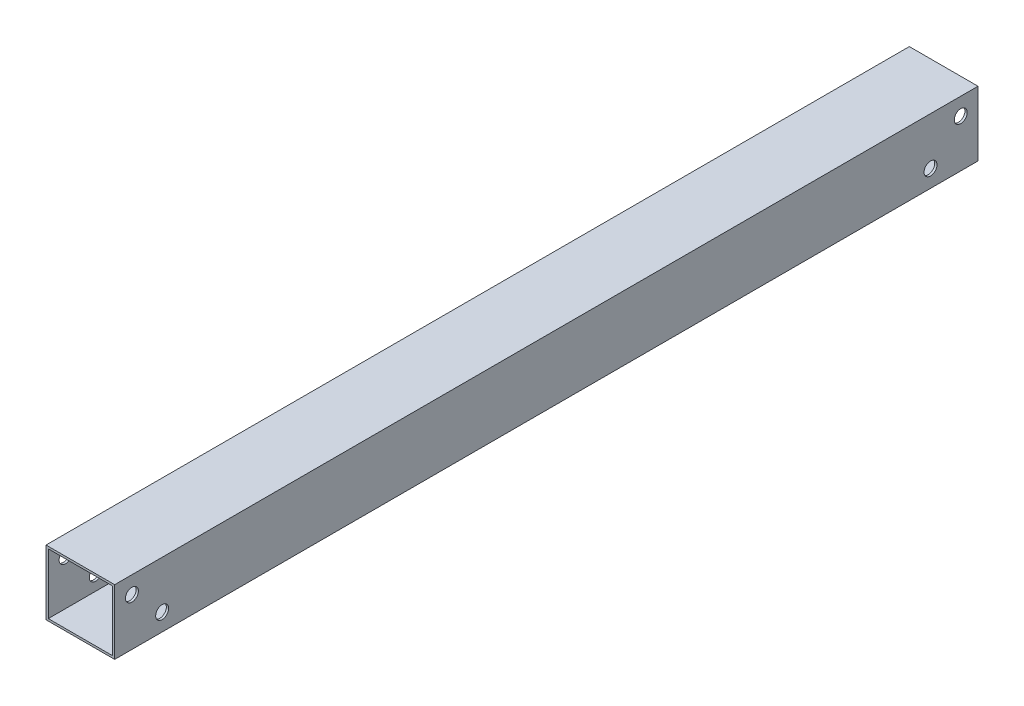
SolidWorks part; units mm, degrees
material "Alliage 1060"
ref_plane "Plan de face" through (0, 0, 0) normal (0, 0, 1) x (1, 0, 0)
ref_plane "Plan de dessus" through (0, 0, 0) normal (0, 1, 0) x (1, 0, 0)
ref_plane "Plan de droite" through (0, 0, 0) normal (1, 0, 0) x (0, 0, -1)
sketch "Esquisse1" plane through (0, 0, 0) normal (0, 0, 1) x (1, 0, 0)
  line L0 (0, 0) -> (15.9091, 15) construction
  line L1 (0, 0) -> (15.9091, 0)
  line L2 (0, 0) -> (0, 15)
  line L3 (0, 15) -> (15.9091, 15)
  line L4 (15.9091, 0) -> (15.9091, 15)
  line L5 (0, 15) -> (15.9091, 0) construction
  line L7 (0.5303, 14.5) -> (15.3788, 14.5)
  line L8 (0.5303, 14.5) -> (0.5303, 0.5)
  line L9 (0.5303, 0.5) -> (15.3788, 0.5)
  line L10 (15.3788, 14.5) -> (15.3788, 0.5)
  line L11 (0.5303, 14.5) -> (15.3788, 0.5) construction
  line L12 (0.5303, 0.5) -> (15.3788, 14.5) construction
  point P5 (7.9546, 7.5)
  dimension "D1" = 14
  dimension "D2" = 15
extrude "Boss.-Extru.1" add sketch "Esquisse1" against normal blind 200
sketch "Esquisse2" plane through (0, 15, 0) normal (0, 1, 0) x (1, 0, 0)
  line L0 (7.9546, 0) -> (7.9546, 200) construction
  line L1 (15.9091, 0) -> (0, 0) construction
  line L2 (15.9091, 200) -> (0, 200) construction
  line L3 (0, 200) -> (7.9546, 200) construction
  line L4 (7.9546, 200) -> (15.9091, 200) construction
  line L5 (15.9091, 200) -> (11.9318, 200) construction
  line L6 (11.9318, 200) -> (11.9318, 0) construction
  line L7 (11.9318, 0) -> (11.9318, 200) construction
  line L8 (11.9318, 200) -> (3.9773, 200) construction
  line L9 (3.9773, 200) -> (3.9773, 0) construction
  line L10 (3.9773, 200) -> (7.9546, 200) construction
  line L11 (7.9546, 200) -> (11.9318, 200) construction
  line L12 (9.9432, 200) -> (9.9432, 0) construction
  line L13 (9.9432, 0) -> (7.9546, 0) construction
  line L14 (7.9546, 0) -> (3.9773, 0) construction
  line L15 (3.9773, 0) -> (5.9659, 0) construction
  line L16 (5.9659, 0) -> (5.9659, 200) construction
  circle A2 centre (5.9659, 122.5818) radius 4
  circle A3 centre (9.9432, 67.5818) radius 4
  dimension "D1" = 8
  dimension "D2" = 8
  dimension "D3" = 55
sketch "Esquisse6" plane through (15.9091, 0, 0) normal (1, 0, 0) x (0, 0, -1)
  line L0 (0, 15) -> (0, 7.5) construction
  line L1 (0, 0) -> (0, 15) construction
  line L2 (0, 7.5) -> (0, 0) construction
  line L3 (0, 0) -> (0, 3.75) construction
  line L5 (200, 0) -> (200, 15) construction
  line L6 (200, 0) -> (200, 7.5) construction
  line L7 (200, 7.5) -> (200, 15) construction
  line L8 (200, 15) -> (200, 11.25) construction
  line L10 (15, 15) -> (15, 0) construction
  line L11 (200, 0) -> (0, 0) construction
  line L12 (0, 15) -> (200, 15) construction
  line L13 (185, 15) -> (185, 0) construction
  circle A0 centre (4, 11) radius 1.5
  circle A1 centre (11, 4) radius 1.5
  circle A2 centre (189, 4) radius 1.5
  circle A3 centre (196, 11) radius 1.5
  point P22 (15, 15)
  point P27 (185, 15)
  dimension "D2" = 3
  dimension "D3" = 3
  dimension "D7" = 3
  dimension "D8" = 3
  dimension "D1" = 15
  dimension "D4" = 4
  dimension "D5" = 4
  dimension "D6" = 15
  dimension "D9" = 4
  dimension "D10" = 4
sketch "Esquisse7" plane through (15.9091, 0, 0) normal (1, 0, 0) x (0, 0, -1)
extrude "Enlèv. mat.-Extru.7" cut sketch "Esquisse6" against normal blind 20
